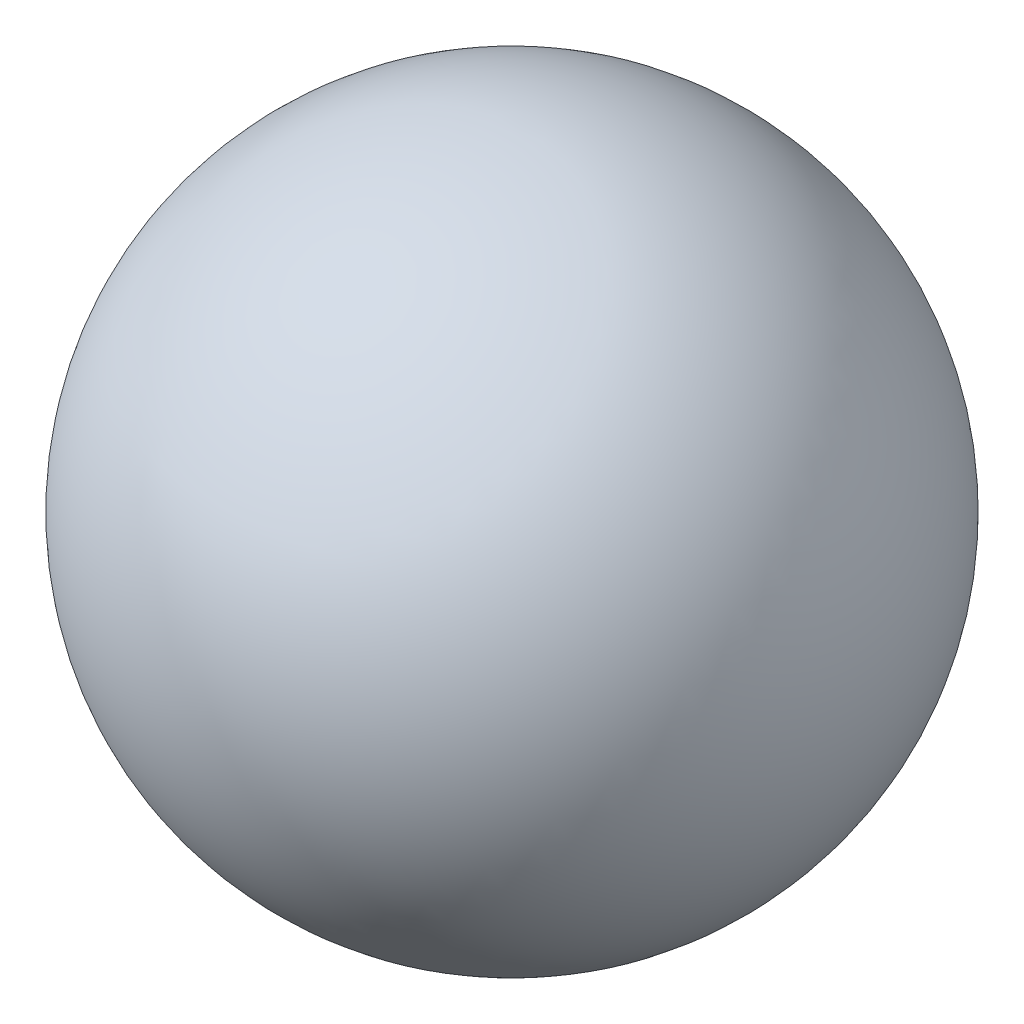
SolidWorks part; units mm, degrees
ref_plane "Front Plane" through (0, 0, 0) normal (0, 0, 1) x (1, 0, 0)
ref_plane "Top Plane" through (0, 0, 0) normal (0, 1, 0) x (1, 0, 0)
ref_plane "Right Plane" through (0, 0, 0) normal (1, 0, 0) x (0, 0, -1)
sketch "Sketch1" plane through (0, 0, 0) normal (0, 0, 1) x (1, 0, 0)
  line L0 (0, 0) -> (0, 53.5105) construction
  line L1 (0, 0) -> (0, -49.811) construction
  line L3 (0, 40.7593) -> (0, 36.1152)
  line L4 (0, -36.1152) -> (0, -40.7593)
  arc A2 (0, 40.7593) -> (0, -40.7593) centre (0, 0) cw
  arc A3 (0, 36.1152) -> (0, -36.1152) centre (0, 0) cw
revolve "Revolve5" add sketch "Sketch1" angle 360 about L0
